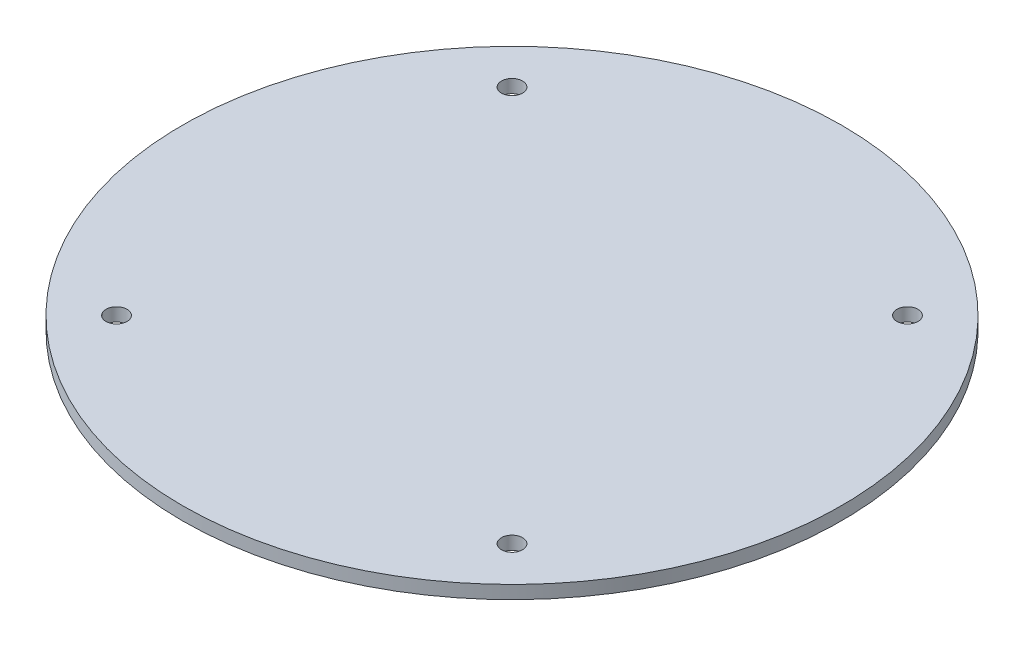
SolidWorks part; units mm, degrees
ref_plane "Plan de face" through (0, 0, 0) normal (0, 0, 1) x (1, 0, 0)
ref_plane "Plan de dessus" through (0, 0, 0) normal (0, 1, 0) x (1, 0, 0)
ref_plane "Plan de droite" through (0, 0, 0) normal (1, 0, 0) x (0, 0, -1)
sketch "Esquisse1" plane through (0, 0, 0) normal (0, 1, 0) x (1, 0, 0)
  line L0 (0, 50) -> (0, -50) construction
  line L1 (-50, 0) -> (50, 0) construction
  circle A0 centre (0, 0) radius 50
  circle A1 centre (-30, 30) radius 1.6
  circle A2 centre (30, 30) radius 1.6
  circle A3 centre (30, -30) radius 1.6
  circle A4 centre (-30, -30) radius 1.6
  point P11 (-26.5961, 8.4608)
  dimension "D1" = 100
  dimension "D2" = 3.2
  dimension "D3" = 30
  dimension "D4" = 30
extrude "Boss.-Extru.1" add sketch "Esquisse1" along normal blind 2
